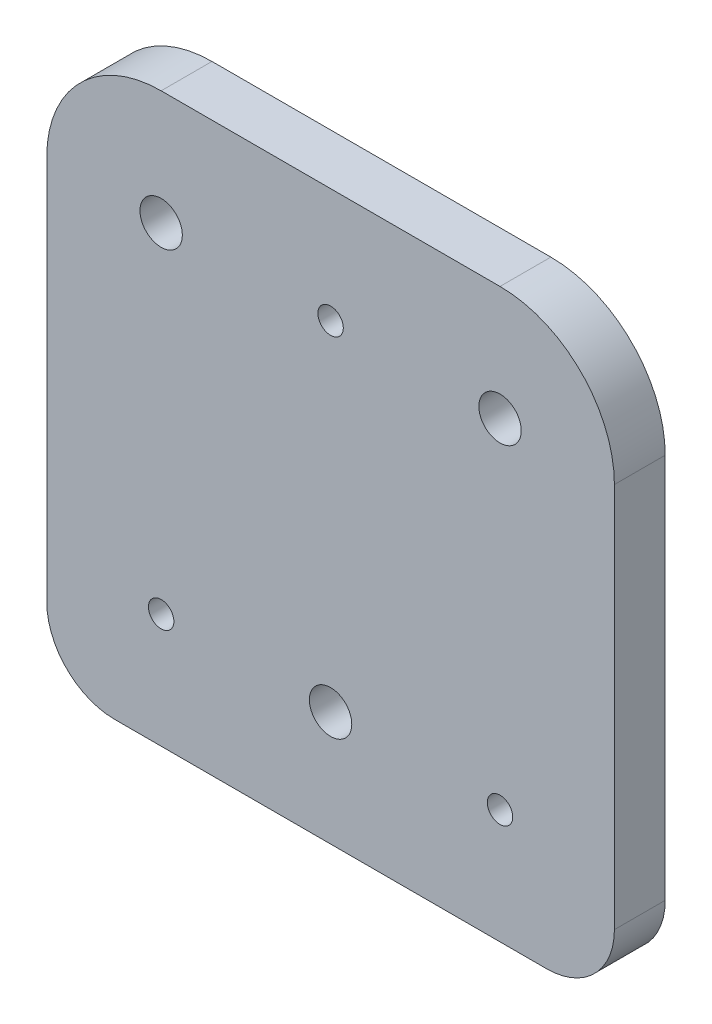
SolidWorks part; units mm, degrees
ref_plane "Plano frontal" through (0, 0, 0) normal (0, 0, 1) x (1, 0, 0)
ref_plane "Plano superior" through (0, 0, 0) normal (0, 1, 0) x (1, 0, 0)
ref_plane "Plano direito" through (0, 0, 0) normal (1, 0, 0) x (0, 0, -1)
sketch "Esboço1" plane through (0, 0, 0) normal (0, 0, 1) x (1, 0, 0)
  line L0 (-20, 33.5) -> (20, 33.5)
  line L1 (-20, 20) -> (20, 20) construction
  line L2 (-20, 20) -> (-20, -20) construction
  line L3 (-20, -20) -> (20, -20) construction
  line L4 (20, 20) -> (20, -20) construction
  line L5 (-20, 20) -> (20, -20) construction
  line L6 (-20, -20) -> (20, 20) construction
  line L9 (33.5, -20) -> (33.5, 20)
  line L10 (20, -33.5) -> (-20, -33.5)
  line L11 (-33.5, -20) -> (-33.5, 20)
  circle A0 centre (-20, 20) radius 2.5
  circle A1 centre (20, 20) radius 2.5
  circle A2 centre (0, -20) radius 2.5
  arc A3 (-20, 33.5) -> (-33.5, 20) centre (-20, 20) ccw
  arc A4 (33.5, 20) -> (20, 33.5) centre (20, 20) ccw
  arc A6 (20, -33.5) -> (33.5, -20) centre (20, -20) ccw
  arc A7 (-33.5, -20) -> (-20, -33.5) centre (-20, -20) ccw
  circle A8 centre (20, 20) radius 13.5 construction
  circle A9 centre (-20, 20) radius 13.5 construction
  point P0 (0, 0)
  point P13 (-8, 22)
  point P14 (0, -20)
  point P15 (32, 22)
  point P18 (12, -22)
  dimension "D3" = 5
  dimension "D1" = 40
  dimension "D2" = 40
  dimension "D4" = 11
extrude "Ressalto-extrusão1" add sketch "Esboço1" along normal blind 6
sketch "Esboço2" plane through (0, 0, 0) normal (0, 0, -1) x (-1, 0, 0)
  line L1 (-33.5, -20) -> (-20, -20)
  line L2 (-33.5, -20) -> (-33.5, -33.5)
  line L3 (-33.5, -33.5) -> (-20, -33.5)
  line L4 (-20, -20) -> (-20, -33.5)
  line L5 (33.5, -20) -> (20, -20)
  line L6 (33.5, -20) -> (33.5, -33.5)
  line L7 (33.5, -33.5) -> (20, -33.5)
  line L8 (20, -20) -> (20, -33.5)
  arc A0 (20, -33.5) -> (33.5, -20) centre (20, -20) ccw construction
extrude "Ressalto-extrusão2" add sketch "Esboço2" against normal up to surface (6 mm away) up to face at (22.5, 20, 6)
fillet "Filete1" radius 8 2 edges at (33.5, -33.5, 3) (-33.5, -33.5, 3)
ref_plane "Plano1" through (0, 0, 0) normal (-1, 0, 0) x (0, 0, 1)
sketch "Esboço3" plane through (0, 0, 0) normal (0, 0, -1) x (-1, 0, 0)
  line L1 (-20, 20) -> (20, 20) construction
  line L2 (-20, 20) -> (-20, -20) construction
  line L3 (-20, -20) -> (20, -20) construction
  line L4 (20, 20) -> (20, -20) construction
  circle A5 centre (0, 20) radius 1.5
  circle A6 centre (20, -20) radius 1.5
  circle A7 centre (-20, -20) radius 1.5
  dimension "D2" = 3
  dimension "D1" = 40
extrude "Corte-extrusão1" cut sketch "Esboço3" against normal up to surface (6 mm away) up to face at (0, -1.0902, 6)
